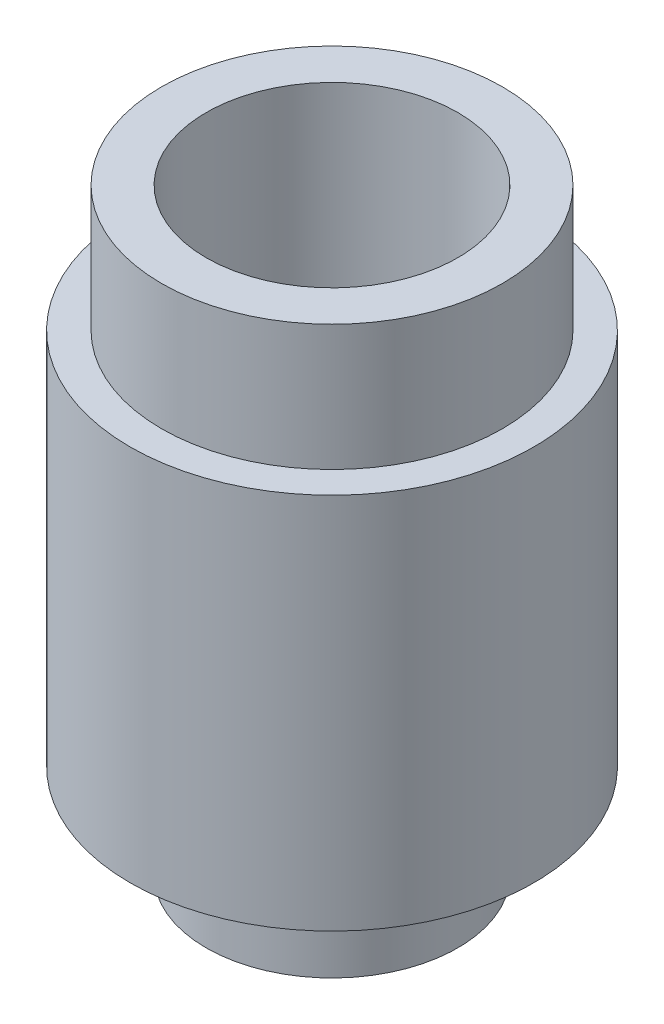
SolidWorks part; units mm, degrees
material "ABS"
ref_plane "Front Plane" through (0, 0, 0) normal (0, 0, 1) x (1, 0, 0)
ref_plane "Top Plane" through (0, 0, 0) normal (0, 1, 0) x (1, 0, 0)
ref_plane "Right Plane" through (0, 0, 0) normal (1, 0, 0) x (0, 0, -1)
sketch "Sketch1" plane through (0, 0, 0) normal (0, 1, 0) x (1, 0, 0)
  circle A0 centre (0, 0) radius 3.85
  dimension "D1" = 7.7
extrude "Boss-Extrude1" add sketch "Sketch1" along normal blind 7.2
ref_plane "Plane1" through (0, 9.6, 0) normal (0, 1, 0) x (1, 0, 0)
sketch "Sketch3" plane through (0, 9.6, 0) normal (0, 1, 0) x (1, 0, 0)
  circle A0 centre (0, 0) radius 3.25
  circle A1 centre (0, 0) radius 2.4
  dimension "D1" = 6.5
  dimension "D2" = 4.8
extrude "Boss-Extrude2" add sketch "Sketch3" against normal blind 8
sketch "Sketch4" plane through (0, 7.2, 0) normal (0, 1, 0) x (1, 0, 0)
  circle A0 centre (0, 0) radius 2.4
  dimension "D1" = 4.8
extrude "Cut-Extrude2" cut sketch "Sketch4" against normal blind 5.6
ref_plane "Plane2" through (0, -1.8, 0) normal (0, -1, 0) x (-1, 0, 0)
sketch "Sketch5" plane through (0, -1.8, 0) normal (0, -1, 0) x (-1, 0, 0)
  circle A0 centre (0, 0) radius 2.4
  circle A1 centre (0, 0) radius 1.7
  dimension "D1" = 4.8
  dimension "D2" = 0.7
extrude "Boss-Extrude3" add sketch "Sketch5" against normal blind 5.6
sketch "Sketch6" plane through (0, 0, 0) normal (0, -1, 0) x (1, 0, 0)
  circle A0 centre (0, 0) radius 1.7
  dimension "D1" = 3.4
extrude "Cut-Extrude3" cut sketch "Sketch6" against normal through all
